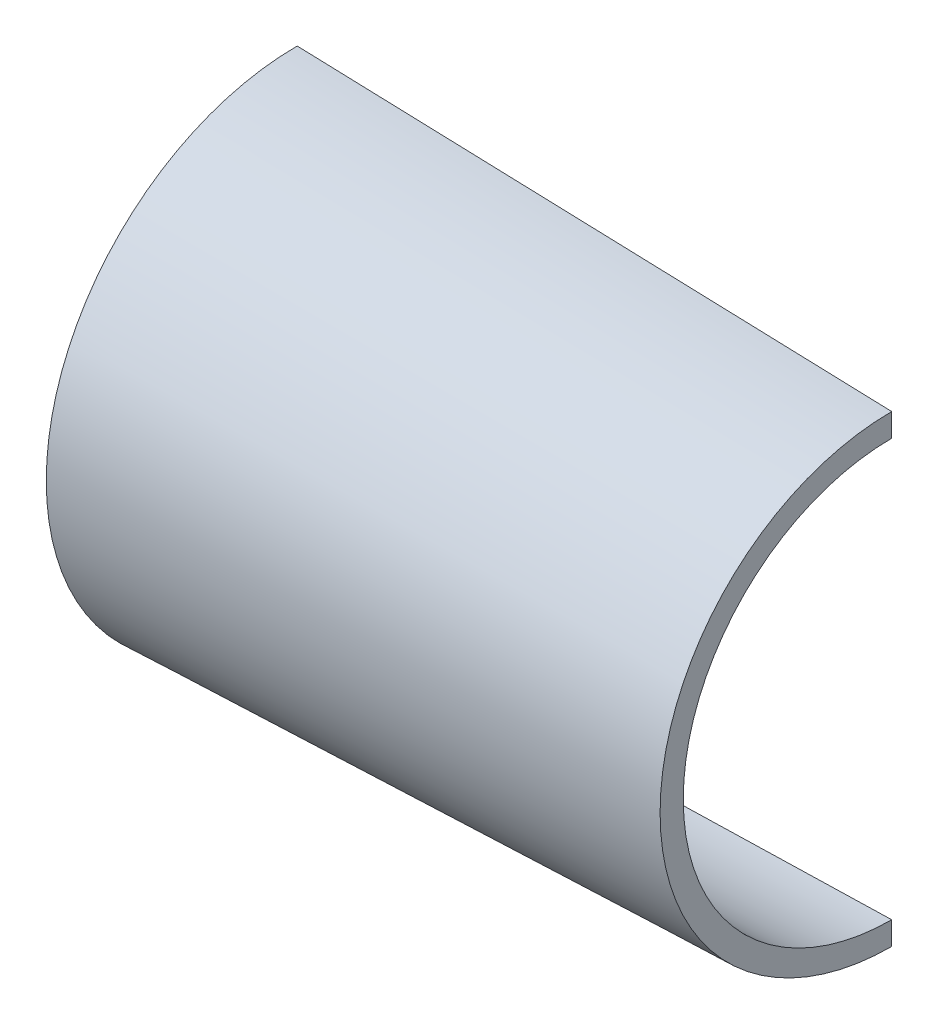
SolidWorks part; units mm, degrees
ref_plane "Front Plane" through (0, 0, 0) normal (0, 0, 1) x (1, 0, 0)
ref_plane "Top Plane" through (0, 0, 0) normal (0, 1, 0) x (1, 0, 0)
ref_plane "Right Plane" through (0, 0, 0) normal (1, 0, 0) x (0, 0, -1)
sketch "Sketch1" plane through (0, 0, 0) normal (0, 0, 1) x (1, 0, 0)
  line L0 (0, 0) -> (4000, 0) construction
  line L1 (1880, 580) -> (1880, 650)
  line L2 (1880, 650) -> (3420, 600)
  line L3 (3420, 600) -> (3420, 540)
  line L4 (3420, 540) -> (1880, 580)
revolve "Revolve1" add sketch "Sketch1" angle 180 about L0
